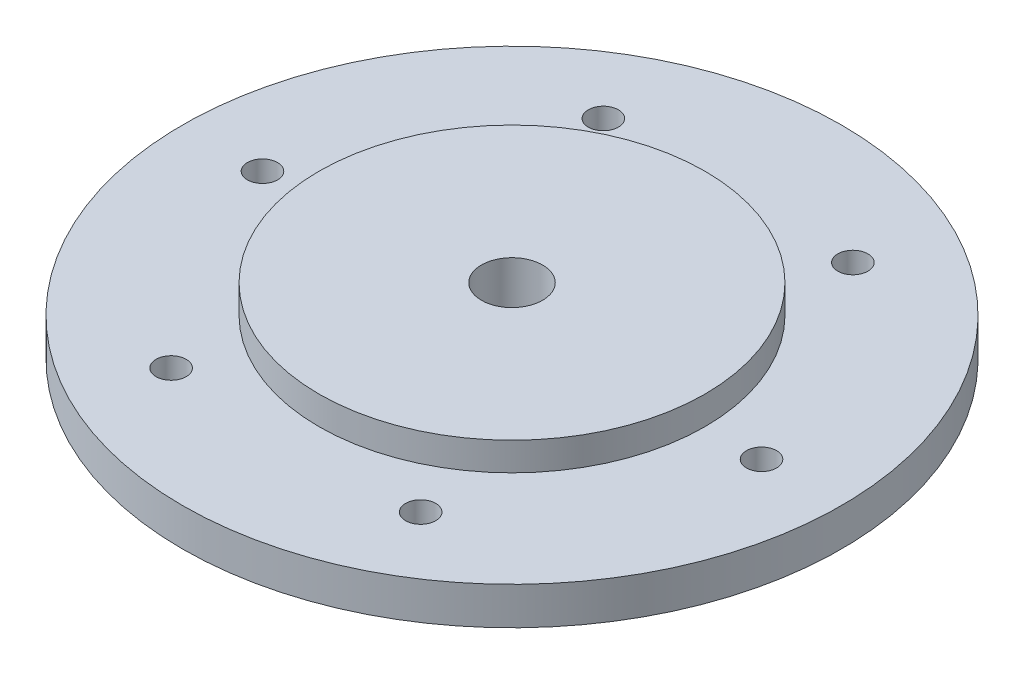
SolidWorks part; units mm, degrees
ref_plane "Спереди" through (0, 0, 0) normal (0, 0, 1) x (1, 0, 0)
ref_plane "Сверху" through (0, 0, 0) normal (0, 1, 0) x (1, 0, 0)
ref_plane "Справа" through (0, 0, 0) normal (1, 0, 0) x (0, 0, -1)
sketch "Эскиз1" plane through (0, 0, 0) normal (0, 1, 0) x (1, 0, 0)
  line L0 (0, 0) -> (-26.5, 0) construction
  circle A0 centre (0, 0) radius 35
  circle A1 centre (0, 0) radius 17.5
  circle A2 centre (0, 0) radius 8.5
  circle A3 centre (0, 0) radius 3.25
  circle A8 centre (-26.5, 0) radius 1.6
  circle A10 centre (0, 0) radius 26.5 construction
  circle A11 centre (-13.25, 22.9497) radius 1.6
  circle A12 centre (13.25, 22.9497) radius 1.6
  circle A13 centre (26.5, 0) radius 1.6
  circle A14 centre (13.25, -22.9497) radius 1.6
  circle A15 centre (-13.25, -22.9497) radius 1.6
  point P23 (0, 0)
  dimension "D1" = 70
  dimension "D2" = 35
  dimension "D3" = 53
  dimension "D4" = 3.2
  dimension "D5" = 17
  dimension "D6" = 6
extrude "Бобышка-Вытянуть1" add sketch "Эскиз1" along normal blind 4 contours A0 A15 A14 A13 A12 A11 A8 A1
sketch "Эскиз2" plane through (0, 4, 0) normal (0, 1, 0) x (1, 0, 0)
  circle A0 centre (0, 0) radius 17.5
  circle A1 centre (0, 0) radius 20.5
  circle A2 centre (0, 0) radius 17.5 construction
  dimension "D1" = 3
extrude "Бобышка-Вытянуть2" add sketch "Эскиз2" along normal blind 3
sketch "Эскиз3" plane through (0, 7, 0) normal (0, 1, 0) x (1, 0, 0)
  circle A0 centre (0, 0) radius 17.5
  circle A2 centre (0, 0) radius 3.25
  circle A3 centre (0, 0) radius 17.5 construction
  circle A4 centre (0, 0) radius 3.25 construction
extrude "Бобышка-Вытянуть3" add sketch "Эскиз3" against normal blind 3
sketch "Эскиз4" plane through (0, 4, 0) normal (0, -1, 0) x (1, 0, 0)
  circle A0 centre (0, 0) radius 3.25
  circle A1 centre (0, 0) radius 8.5
  circle A2 centre (0, 0) radius 3.25 construction
  dimension "D1" = 17
extrude "Бобышка-Вытянуть4" add sketch "Эскиз4" along normal blind 4
